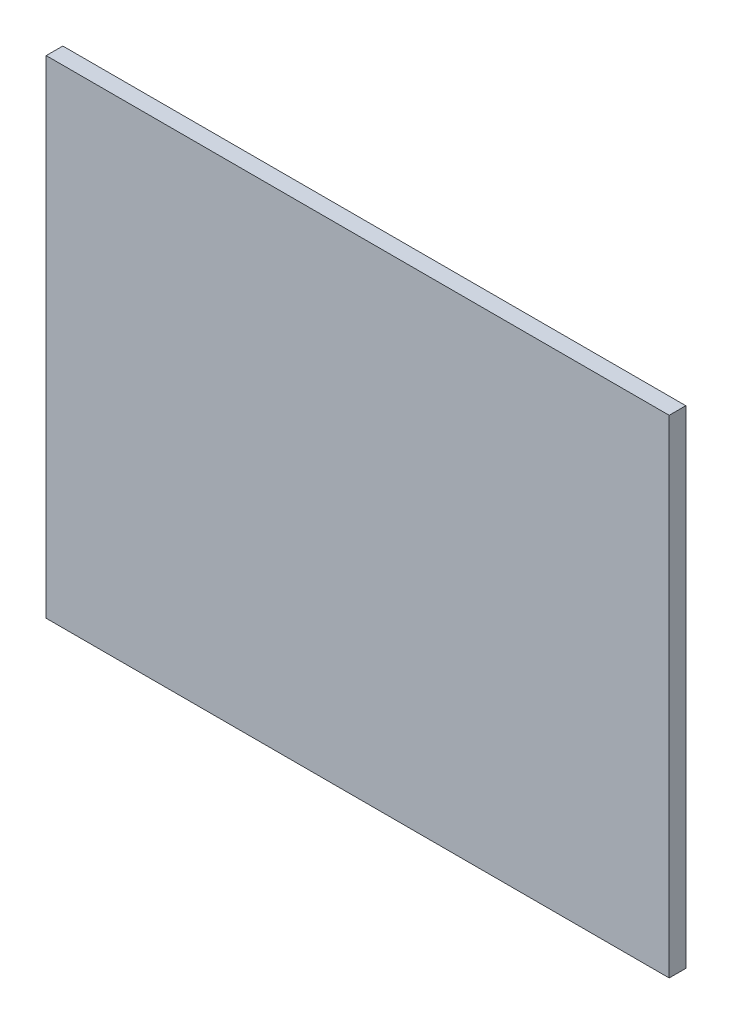
SolidWorks part; units mm, degrees
material "Plain Carbon Steel"
ref_plane "Front Plane" through (0, 0, 0) normal (0, 0, 1) x (1, 0, 0)
ref_plane "Top Plane" through (0, 0, 0) normal (0, 1, 0) x (1, 0, 0)
ref_plane "Right Plane" through (0, 0, 0) normal (1, 0, 0) x (0, 0, -1)
sketch "Sketch1" plane through (0, 0, 0) normal (0, 0, 1) x (1, 0, 0)
  line L1 (-112.5, -88) -> (112.5, -88)
  line L2 (-112.5, -88) -> (-112.5, 88)
  line L3 (-112.5, 88) -> (112.5, 88)
  line L4 (112.5, -88) -> (112.5, 88)
  line L5 (-112.5, -88) -> (112.5, 88) construction
  line L6 (-112.5, 88) -> (112.5, -88) construction
  point P0 (0, 0)
  dimension "D1" = 225
  dimension "D2" = 176
extrude "Boss-Extrude1" add sketch "Sketch1" along normal blind 6
